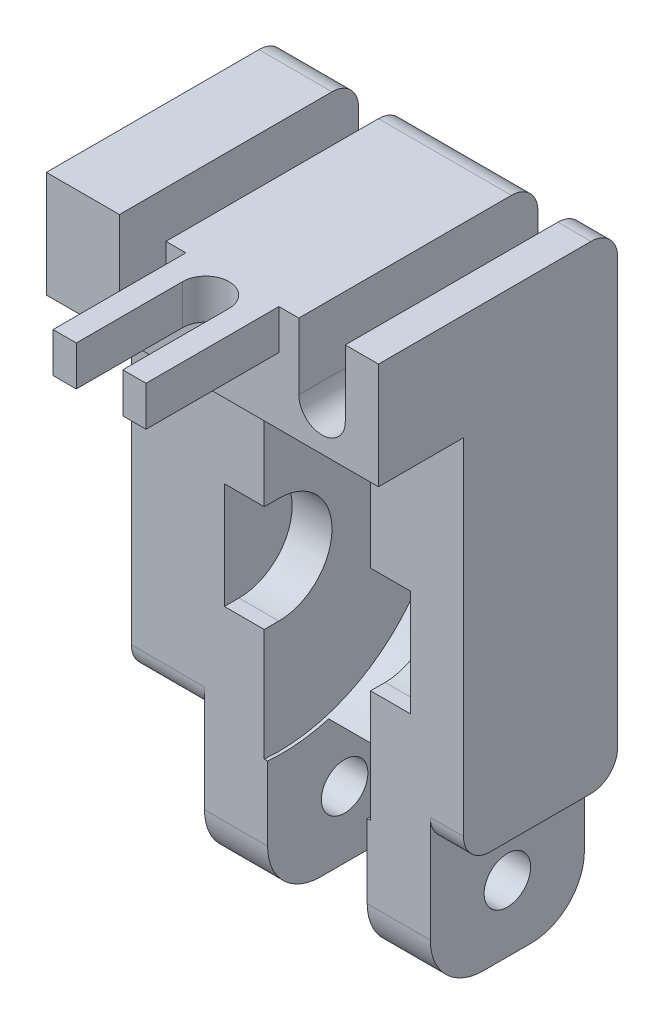
SolidWorks part; units mm, degrees
ref_plane "Front Plane" through (0, 0, 0) normal (0, 0, 1) x (1, 0, 0)
ref_plane "Top Plane" through (0, 0, 0) normal (0, 1, 0) x (1, 0, 0)
ref_plane "Right Plane" through (0, 0, 0) normal (1, 0, 0) x (0, 0, -1)
sketch "Sketch1" plane through (0, 0, 0) normal (0, 0, 1) x (1, 0, 0)
  line L1 (0, 0) -> (-25, 0)
  line L2 (0, 0) -> (0, 46)
  line L3 (0, 46) -> (-25, 46)
  line L4 (-25, 0) -> (-25, 46)
  dimension "D1" = 25
  dimension "D2" = 46
extrude "Boss-Extrude1" add sketch "Sketch1" along normal blind 18
sketch "Sketch2" plane through (0, 0, 18) normal (0, 0, 1) x (1, 0, 0)
  line L0 (0, 46) -> (-25, 46) construction
  line L1 (-14.5, 46) -> (-7.5, 46)
  line L2 (-14.5, 46) -> (-14.5, 43)
  line L3 (-14.5, 43) -> (-7.5, 43)
  line L4 (-7.5, 46) -> (-7.5, 43)
  line L6 (-11, 43) -> (-11, 46) construction
  line L8 (-25, 46) -> (-25, 0) construction
  dimension "D1" = 7
  dimension "D2" = 3
  dimension "D3" = 14
extrude "Boss-Extrude2" add sketch "Sketch2" along normal blind 10
sketch "Sketch3" plane through (0, 46, 0) normal (0, 1, 0) x (1, 0, 0)
  line L0 (-11, -28) -> (-11, -20) construction
  line L1 (-7.5, -28) -> (-14.5, -28) construction
  line L2 (-12.75, -28) -> (-12.75, -20)
  line L3 (-9.25, -28) -> (-9.25, -20)
  arc A0 (-12.75, -28) -> (-9.25, -28) centre (-11, -28) ccw
  arc A1 (-9.25, -20) -> (-12.75, -20) centre (-11, -20) ccw
  point P4 (-11, -24)
  dimension "D1" = 1.75
  dimension "D2" = 8
extrude "Cut-Extrude1" cut sketch "Sketch3" against normal blind 10
ref_plane "Plane1" through (-11, 0, 0) normal (-1, 0, 0) x (0, 0, 1)
sketch "Sketch5" plane through (-11, 0, 0) normal (-1, 0, 0) x (0, 0, 1)
  line L2 (18, 46) -> (0, 46) construction
  line L3 (18, 46) -> (18, 0) construction
  circle A0 centre (10.5, 22) radius 12.5
  dimension "D1" = 25
  dimension "D3" = 24
  dimension "D2" = 7.5
extrude "Cut-Extrude2" cut sketch "Sketch5" against normal blind 4 and the other way blind 4
sketch "Sketch7" plane through (-11, 0, 0) normal (-1, 0, 0) x (0, 0, 1)
  line L0 (10.5, 22) -> (19.8045, 22) construction
  line L1 (10.5, 26) -> (19.8045, 26)
  line L2 (10.5, 18) -> (19.8045, 18)
  arc A0 (10.5, 26) -> (10.5, 18) centre (10.5, 22) ccw
  arc A1 (19.8045, 18) -> (19.8045, 26) centre (19.8045, 22) ccw
  point P3 (15.1523, 22)
  dimension "D1" = 4
extrude "Cut-Extrude3" cut sketch "Sketch7" against normal offset from surface 3 and the other way offset from surface (7 mm away) 3 up to face at (-7, 22, 8.6502) offset beyond the face yes other way up to face at (-15, 22, 8.6502)
sketch "Sketch8" plane through (-25, 0, 0) normal (-1, 0, 0) x (0, 0, 1)
  line L1 (0, 46) -> (0, 0) construction
  line L2 (18, 46) -> (0, 46) construction
  circle A0 centre (5.8, 5) radius 1.75
  dimension "D1" = 3.5
  dimension "D3" = 5.8
  dimension "D2" = 41
extrude "Cut-Extrude4" cut sketch "Sketch8" against normal up to next
sketch "Sketch9" plane through (-25, 0, 0) normal (-1, 0, 0) x (0, 0, 1)
  line L0 (18, 46) -> (0, 46) construction
  line L1 (18, 0) -> (11.6, 0)
  line L2 (18, 0) -> (18, 38)
  line L3 (18, 38) -> (11.6, 38)
  line L4 (11.6, 0) -> (11.6, 38)
  line L5 (0, 46) -> (0, 0) construction
  dimension "D1" = 8
  dimension "D2" = 11.6
extrude "Cut-Extrude5" cut sketch "Sketch9" against normal blind 36
sketch "Sketch10" plane through (0, 0, 11.6) normal (0, 0, 1) x (1, 0, 0)
  line L2 (0, 0) -> (-25, 0) construction
  line L3 (-14.75, 0) -> (-7.25, 0)
  line L4 (-14.75, 0) -> (-14.75, 10)
  line L5 (-14.75, 10) -> (-7.25, 10)
  line L7 (-7, 18) -> (-7, 9.5485) construction
  line L8 (0, 0) -> (-2.5, 0)
  line L9 (0, 0) -> (0, 10)
  line L10 (0, 10) -> (-2.5, 10)
  line L11 (-2.5, 0) -> (-2.5, 10)
  line L12 (-25, 0) -> (-19.5, 0)
  line L13 (-25, 0) -> (-25, 10)
  line L14 (-25, 10) -> (-19.5, 10)
  line L15 (-19.5, 0) -> (-19.5, 10)
  line L16 (-15, 18) -> (-15, 9.5485) construction
  line L17 (-7.25, 0) -> (-7.25, 10)
  dimension "D1" = 10
  dimension "D2" = 4.5
  dimension "D3" = 4.5
  dimension "D4" = 7.5
  dimension "D5" = 0.25
extrude "Cut-Extrude6" cut sketch "Sketch10" against normal blind 32
fillet "Fillet1" radius 4 4 edges at (-4.875, 0, 11.6) (-17.125, 0, 11.6) (-4.875, 0, 0) (-17.125, 0, 0)
fillet "Fillet2" radius 2 6 edges at (-1.25, 10, 11.6) (-22.25, 10, 11.6) (-22.25, 10, 0) (-1.25, 10, 0) (-11, 10, 0) (-12.5, 46, 0)
sketch "Sketch11" plane through (0, 0, 18) normal (0, 0, 1) x (1, 0, 0)
  line L0 (-9.25, 46) -> (-12.75, 46) construction
  line L1 (-19.5, 41) -> (-19.5, 46.5149)
  line L2 (-19.5, 46.5149) -> (-16, 46.5149)
  line L3 (-16, 46.5149) -> (-16, 41)
  line L4 (-6, 41) -> (-6, 46.5149)
  line L5 (-6, 46.5149) -> (-2.5, 46.5149)
  line L6 (-2.5, 46.5149) -> (-2.5, 41)
  line L7 (0, 46) -> (-7.5, 46) construction
  arc A0 (-6, 41) -> (-2.5, 41) centre (-4.25, 41) ccw
  arc A1 (-19.5, 41) -> (-16, 41) centre (-17.75, 41) ccw
  point P4 (-11, 46)
  dimension "D1" = 3.5
  dimension "D2" = 13.5
  dimension "D3" = 6.75
  dimension "D4" = 5
extrude "Cut-Extrude7" cut sketch "Sketch11" against normal blind 32
